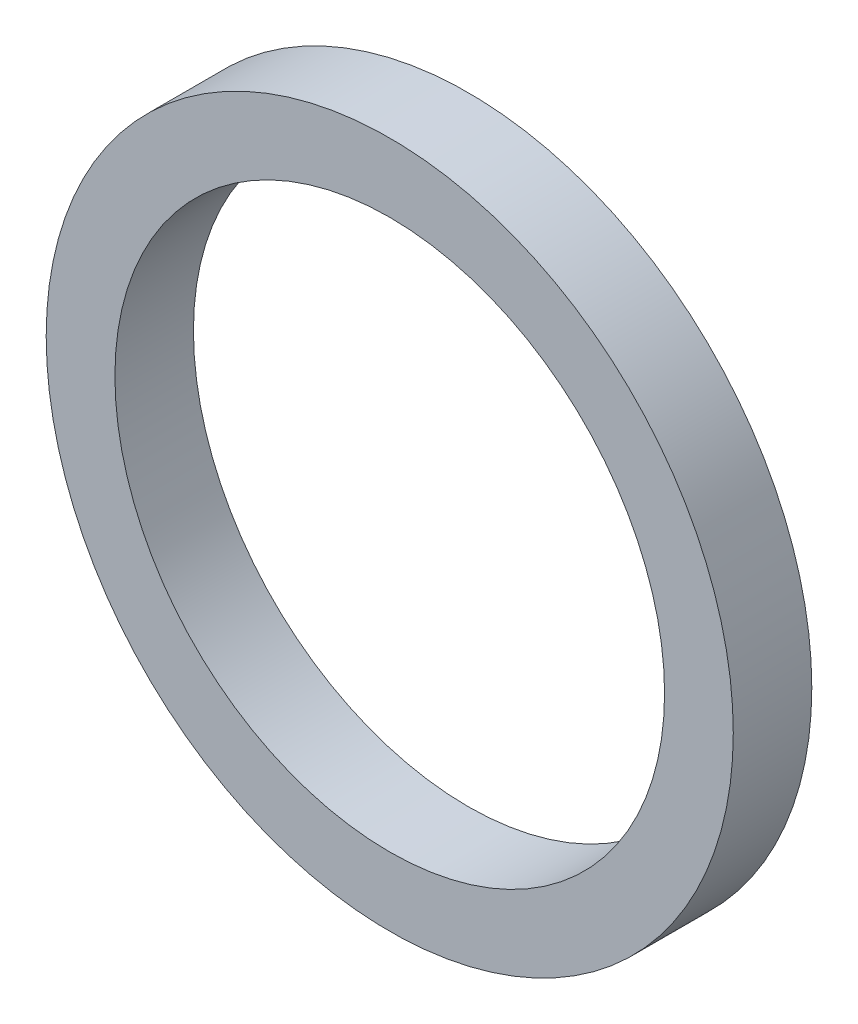
SolidWorks part; units mm, degrees
ref_plane "Front Plane" through (0, 0, 0) normal (1, 0, 0) x (0, 1, 0)
ref_plane "Top Plane" through (0, 0, 0) normal (0, 0, 1) x (0, 1, 0)
ref_plane "Right Plane" through (0, 0, 0) normal (0, 1, 0) x (-1, 0, 0)
sketch "Sketch1" plane through (0, 0, 0) normal (0, 0, 1) x (0, 1, 0)
  circle A0 centre (0, 0) radius 14
  circle A1 centre (0, 0) radius 17.5
  point P5 (0, 0)
  point P6 (0, 0)
  dimension "D1" = 28
  dimension "D2" = 3.5
extrude "Boss-Extrude1" add sketch "Sketch1" along normal blind 4
